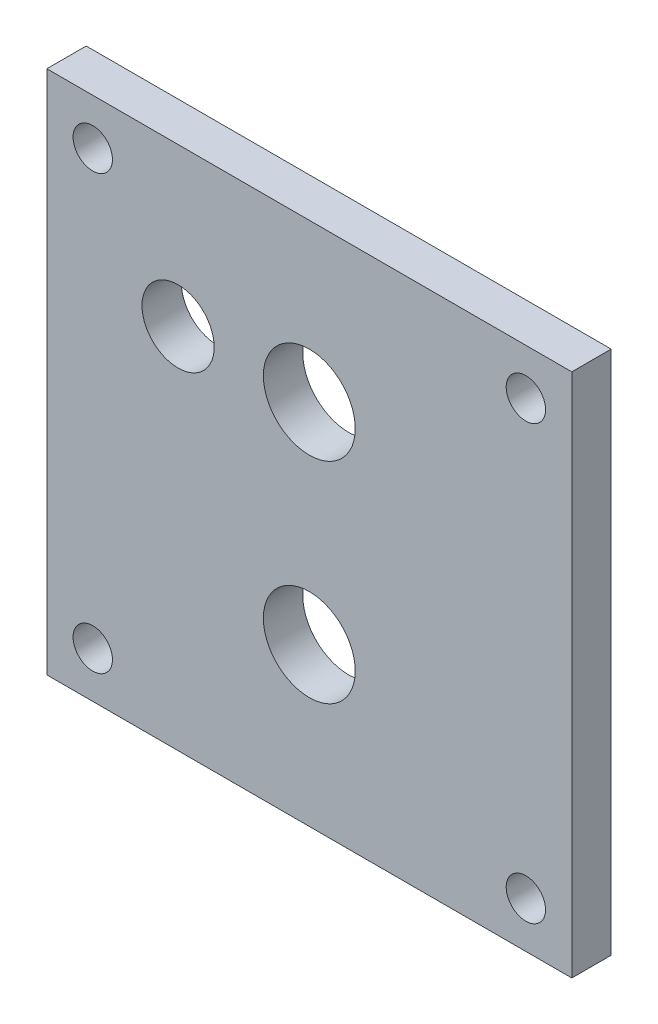
SolidWorks part; units mm, degrees
ref_plane "Front Plane" through (0, 0, 0) normal (0, 0, 1) x (1, 0, 0)
ref_plane "Top Plane" through (0, 0, 0) normal (0, 1, 0) x (1, 0, 0)
ref_plane "Right Plane" through (0, 0, 0) normal (1, 0, 0) x (0, 0, -1)
sketch "Sketch1" plane through (0, 0, 0) normal (0, 0, 1) x (1, 0, 0)
  line L1 (-63.5, 63.5) -> (63.5, 63.5)
  line L2 (-63.5, 63.5) -> (-63.5, -63.5)
  line L3 (-63.5, -63.5) -> (63.5, -63.5)
  line L4 (63.5, 63.5) -> (63.5, -63.5)
  line L5 (-63.5, 63.5) -> (63.5, -63.5) construction
  line L6 (-63.5, -63.5) -> (63.5, 63.5) construction
  point P0 (0, 0)
  dimension "D1" = 127
  dimension "D2" = 127
extrude "Boss-Extrude1" add sketch "Sketch1" along normal blind 9.525
sketch "Sketch2" plane through (0, 0, 0) normal (0, 0, -1) x (-1, 0, 0)
  line L4 (-63.5, 63.5) -> (63.5, 63.5) construction
  line L5 (63.5, -63.5) -> (-63.5, -63.5) construction
  line L6 (-63.5, -63.5) -> (-63.5, 63.5) construction
  line L7 (63.5, 63.5) -> (63.5, -63.5) construction
  circle A0 centre (0, 25.4) radius 11.1125
  circle A1 centre (31.75, 25.4) radius 8.7312
  circle A2 centre (0, -25.4) radius 11.1125
  dimension "D1" = 22.225
  dimension "D2" = 38.1
  dimension "D4" = 17.4625
  dimension "D5" = 38.1
  dimension "D6" = 63.5
  dimension "D7" = 22.225
  dimension "D8" = 63.5
  dimension "D9" = 31.75
  dimension "D3" = 38.1
extrude "Cut-Extrude1" cut sketch "Sketch2" against normal up to surface (9.525 mm away) up to face at (0, 0, 9.525)
sketch "Sketch3" plane through (0, 0, 0) normal (0, 0, -1) x (-1, 0, 0)
  line L0 (-63.5, 63.5) -> (63.5, 63.5) construction
  line L1 (63.5, 63.5) -> (63.5, -63.5) construction
  line L2 (0, -63.5) -> (0, 63.5) construction
  line L3 (63.5, -63.5) -> (-63.5, -63.5) construction
  line L4 (63.5, 0) -> (-63.5, 0) construction
  line L5 (-63.5, -63.5) -> (-63.5, 63.5) construction
  circle A0 centre (52.3875, 52.3875) radius 4.7625
  circle A1 centre (52.3875, -52.3875) radius 4.7625
  circle A2 centre (-52.3875, 52.3875) radius 4.7625
  circle A3 centre (-52.3875, -52.3875) radius 4.7625
  dimension "D1" = 9.525
  dimension "D2" = 11.1125
  dimension "D3" = 11.1125
extrude "Cut-Extrude2" cut sketch "Sketch3" against normal up to surface (9.525 mm away) up to face at (11.1125, -25.4, 9.525)
